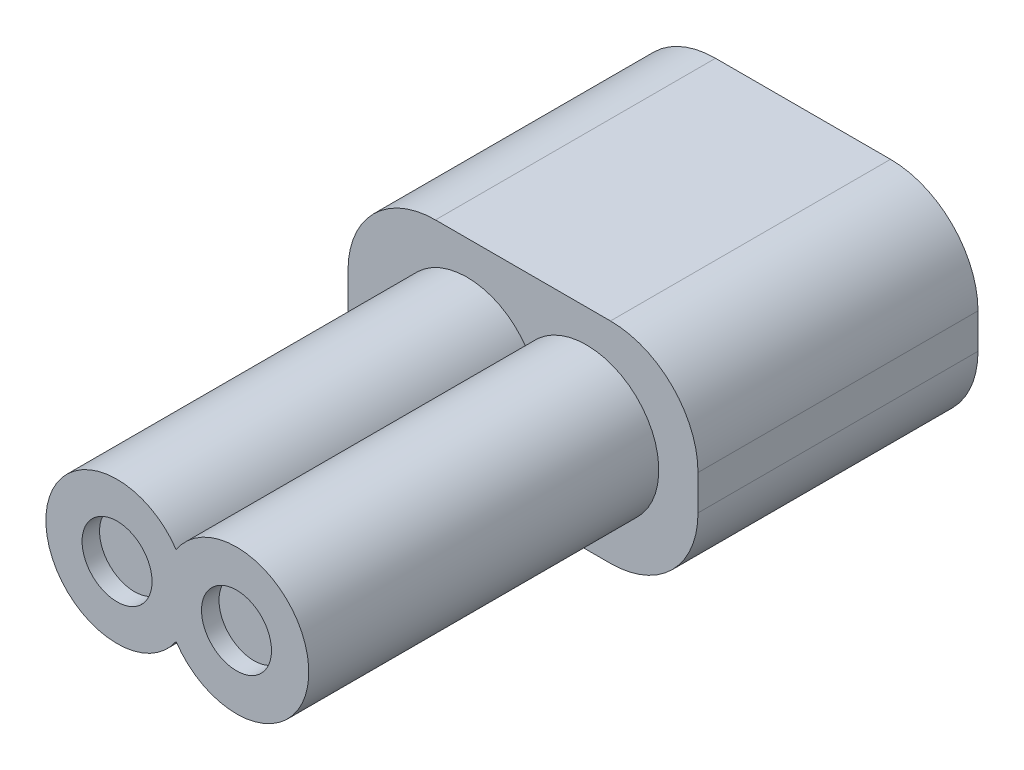
SolidWorks part; units mm, degrees
ref_plane "正面" through (0, 0, 0) normal (0, 0, 1) x (1, 0, 0)
ref_plane "平面" through (0, 0, 0) normal (0, 1, 0) x (1, 0, 0)
ref_plane "右側面" through (0, 0, 0) normal (1, 0, 0) x (0, 0, -1)
sketch "ｽｹｯﾁ1" plane through (0, 0, 0) normal (0, 0, 1) x (1, 0, 0)
  line L1 (5, 0) -> (15, 0)
  line L2 (0, 5) -> (0, 7)
  line L3 (5, 12) -> (15, 12)
  line L4 (20, 5) -> (20, 7)
  arc A0 (15, 0) -> (20, 5) centre (15, 5) ccw
  arc A1 (15, 12) -> (20, 7) centre (15, 7) cw
  arc A2 (5, 0) -> (0, 5) centre (5, 5) cw
  arc A3 (0, 7) -> (5, 12) centre (5, 7) cw
  point P9 (20, 12)
  point P12 (0, 0)
  point P15 (0, 12)
  dimension "D3" = 5
  dimension "D1" = 12
  dimension "D2" = 20
extrude "ﾎﾞｽ - 押し出し1" add sketch "ｽｹｯﾁ1" along normal blind 16
sketch "ｽｹｯﾁ3" plane through (0, 0, 16) normal (0, 0, 1) x (1, 0, 0)
  arc A2 (10.1785, 3.7279) -> (10.1785, 8.2721) centre (13.6288, 6) ccw
  arc A3 (10.1785, 8.2721) -> (10.1785, 3.7279) centre (6.8039, 6) ccw
  point P6 (6.8039, 6)
  point P8 (13.6288, 6)
  point P14 (9.7381, 6.8971)
  point P15 (16.6232, 6.9155)
  point P17 (17.76, 6)
extrude "ﾎﾞｽ - 押し出し3" add sketch "ｽｹｯﾁ3" along normal blind 20
sketch "ｽｹｯﾁ4" plane through (0, 0, 36) normal (0, 0, 1) x (1, 0, 0)
  circle A0 centre (6.8039, 6) radius 2
  arc A1 (10.1785, 8.2721) -> (10.1785, 3.7279) centre (6.8039, 6) ccw construction
  circle A2 centre (13.6288, 6) radius 2
  arc A5 (10.1785, 3.7279) -> (10.1785, 8.2721) centre (13.6288, 6) ccw construction
  dimension "D1" = 4
  dimension "D2" = 4
extrude "ｶｯﾄ - 押し出し1" cut sketch "ｽｹｯﾁ4" against normal blind 1
